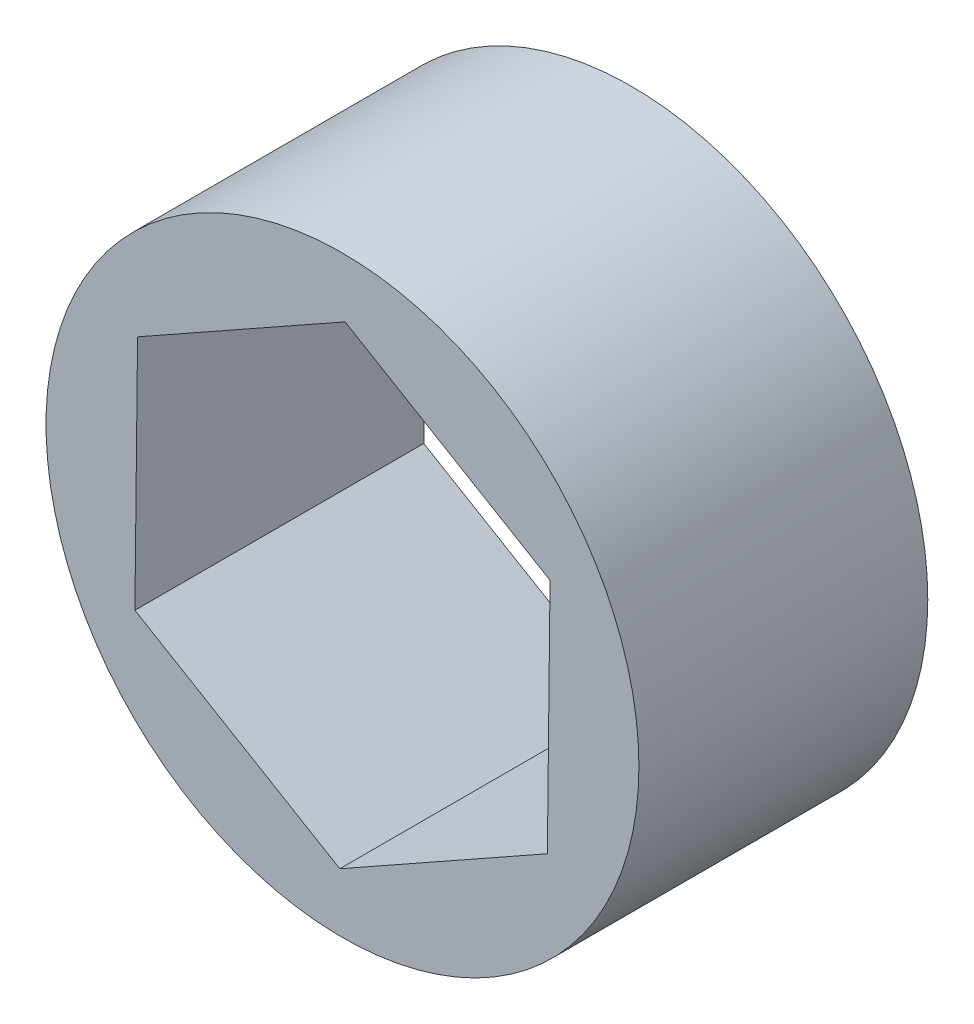
SolidWorks part; units mm, degrees
ref_plane "Alzado" through (0, 0, 0) normal (0, 0, 1) x (1, 0, 0)
ref_plane "Planta" through (0, 0, 0) normal (0, 1, 0) x (1, 0, 0)
ref_plane "Vista lateral" through (0, 0, 0) normal (1, 0, 0) x (0, 0, -1)
sketch "Croquis1" plane through (0, 0, 0) normal (0, 0, 1) x (1, 0, 0)
  line L1 (6.4973, -3.8489) -> (6.5819, 3.7023)
  line L2 (6.5819, 3.7023) -> (0.0846, 7.5513)
  line L3 (0.0846, 7.5513) -> (-6.4973, 3.8489)
  line L4 (-6.4973, 3.8489) -> (-6.5819, -3.7023)
  line L5 (-6.5819, -3.7023) -> (-0.0846, -7.5513)
  line L6 (-0.0846, -7.5513) -> (6.4973, -3.8489)
  circle A0 centre (0, 0) radius 9.4
  circle A1 centre (0, 0) radius 6.54 construction
  point P3 (6.5396, -0.0733)
  dimension "D1" = 18.8
  dimension "13.08" = 13.08
extrude "Saliente-Extruir2" add sketch "Croquis1" along normal blind 9.16
